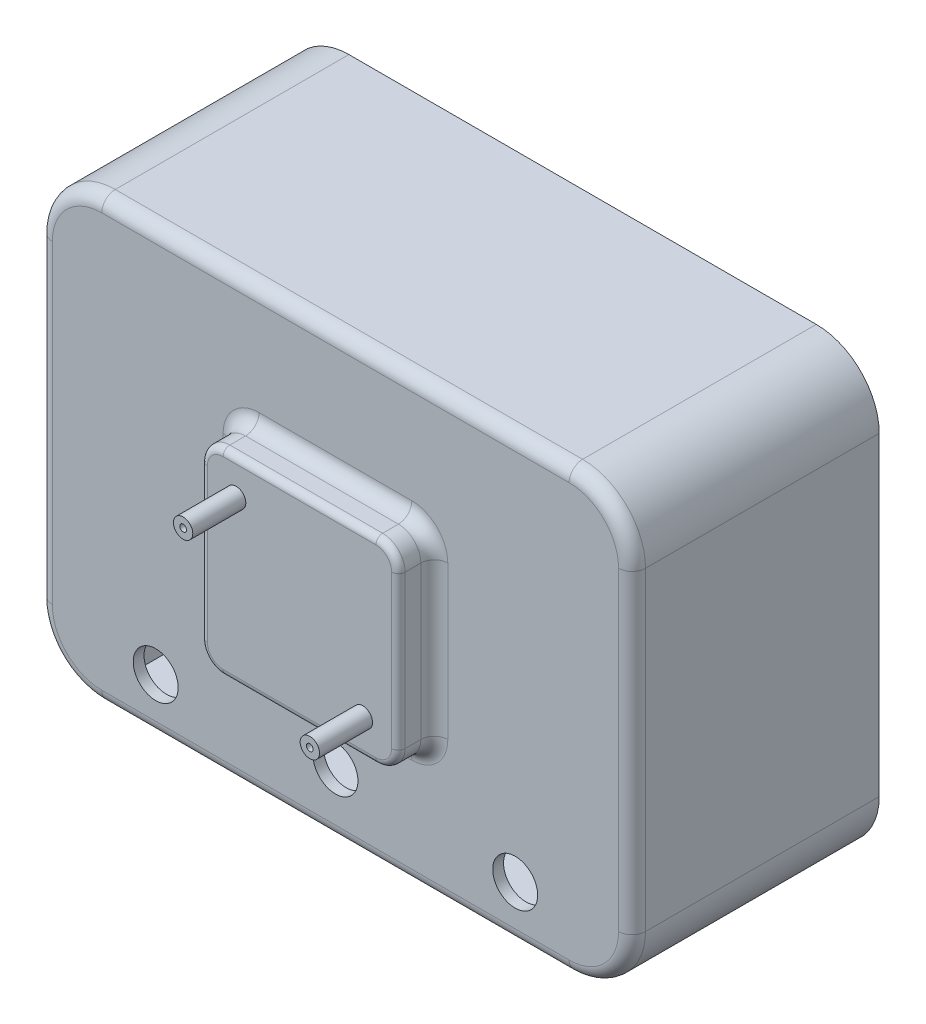
SolidWorks part; units mm, degrees
ref_plane "Front Plane" through (0, 0, 0) normal (0, 0, 1) x (1, 0, 0)
ref_plane "Top Plane" through (0, 0, 0) normal (0, 1, 0) x (1, 0, 0)
ref_plane "Right Plane" through (0, 0, 0) normal (1, 0, 0) x (0, 0, -1)
sketch "Sketch1" plane through (0, 0, 0) normal (0, 0, 1) x (1, 0, 0)
  line L1 (-66, -49) -> (66, -49)
  line L2 (-66, -49) -> (-66, 49)
  line L3 (-66, 49) -> (66, 49)
  line L4 (66, -49) -> (66, 49)
extrude "Boss-Extrude1" add sketch "Sketch1" along normal blind 55
fillet "Fillet1" radius 14 4 edges at (-66, 49, 27.5) (66, 49, 27.5) (66, -49, 27.5) (-66, -49, 27.5)
sketch "Sketch7" plane through (0, 0, 0) normal (0, 0, 1) x (1, 0, 0)
  circle A0 centre (-27.75, -42.789) radius 6
  circle A1 centre (27.75, -42.789) radius 6
  circle A2 centre (-27.75, 42.789) radius 6
  circle A3 centre (27.75, 42.789) radius 6
extrude "Boss-Extrude2" add sketch "Sketch7" along normal blind 6
sketch "Sketch8" plane through (0, 0, 6) normal (0, 0, 1) x (1, 0, 0)
  circle A0 centre (-27.75, -42.789) radius 2.25
  circle A1 centre (27.75, -42.789) radius 2.25
  circle A2 centre (-27.75, 42.789) radius 2.25
  circle A3 centre (27.75, 42.789) radius 2.25
extrude "Cut-Extrude10" cut sketch "Sketch8" against normal blind 6.2
sketch "Sketch9" plane through (0, 0, 6) normal (0, 0, 1) x (1, 0, 0)
  circle A0 centre (-27.75, -42.789) radius 4
  circle A1 centre (27.75, -42.789) radius 4
  circle A2 centre (-27.75, 42.789) radius 4
  circle A3 centre (27.75, 42.789) radius 4
extrude "Cut-Extrude11" cut sketch "Sketch9" against normal blind 3
fillet "Fillet2" radius 3 8 edges at (-66, 0, 55) (0, -49, 55) (66, 0, 55) (0, 49, 55) (-61.8995, -44.8995, 55) (61.8995, -44.8995, 55) (61.8995, 44.8995, 55) (-61.8995, 44.8995, 55)
sketch "Sketch10" plane through (0, 0, 55) normal (0, 0, 1) x (1, 0, 0)
  line L1 (-22, -22) -> (22, -22)
  line L2 (-22, -22) -> (-22, 22)
  line L3 (-22, 22) -> (22, 22)
  line L4 (22, -22) -> (22, 22)
extrude "Boss-Extrude3" add sketch "Sketch10" along normal blind 8
fillet "Fillet3" radius 5 4 edges at (-22, 22, 59) (22, 22, 59) (22, -22, 59) (-22, -22, 59)
fillet "Fillet4" radius 1.5 8 edges at (-22, 0, 63) (0, -22, 63) (22, 0, 63) (0, 22, 63) (-20.5355, -20.5355, 63) (20.5355, -20.5355, 63) (20.5355, 20.5355, 63) (-20.5355, 20.5355, 63)
sketch "Sketch11" plane through (0, 0, 63) normal (0, 0, 1) x (1, 0, 0)
  circle A0 centre (-14.1, 14.1) radius 2.15
  circle A1 centre (14.1, -14.1) radius 2.15
extrude "Boss-Extrude4" add sketch "Sketch11" along normal blind 11.8
sketch "Sketch12" plane through (0, 0, 74.8) normal (0, 0, 1) x (1, 0, 0)
  circle A0 centre (-14.1, 14.1) radius 0.75
  circle A1 centre (14.1, -14.1) radius 0.75
extrude "Cut-Extrude12" cut sketch "Sketch12" against normal blind 11.3
sketch "Sketch13" plane through (0, 0, 55) normal (0, 0, 1) x (1, 0, 0)
  circle A0 centre (-40, -37) radius 5
  circle A1 centre (40, -37) radius 5
  circle A2 centre (0, -35) radius 5
extrude "Cut-Extrude13" cut sketch "Sketch13" against normal blind 3.2
fillet "Fillet5" radius 3 8 edges at (-22, 0, 55) (0, -22, 55) (22, 0, 55) (0, 22, 55) (-20.5355, 20.5355, 55) (20.5355, 20.5355, 55) (20.5355, -20.5355, 55) (-20.5355, -20.5355, 55)
sketch "Sketch14" plane through (0, 0, 0) normal (0, 0, -1) x (-1, 0, 0)
  line L1 (-52, -46) -> (52, -46)
  line L2 (-52, -46) -> (-52, 46)
  line L3 (-52, 46) -> (52, 46)
  line L4 (52, -46) -> (52, 46)
extrude "Cut-Extrude14" cut sketch "Sketch14" against normal blind 52.6
sketch "Sketch15" plane through (0, 0, 0) normal (0, 0, -1) x (-1, 0, 0)
  line L1 (-63, -35) -> (63, -35)
  line L2 (-63, -35) -> (-63, 35)
  line L3 (-63, 35) -> (63, 35)
  line L4 (63, -35) -> (63, 35)
extrude "Cut-Extrude15" cut sketch "Sketch15" against normal blind 52.6
sketch "Sketch17" plane through (0, 0, 0) normal (0, 0, 1) x (1, 0, 0)
  circle A0 centre (-27.75, -42.789) radius 6.2
  circle A1 centre (27.75, -42.789) radius 6.2
  circle A2 centre (-27.75, 42.789) radius 6.2
  circle A3 centre (27.75, 42.789) radius 6.2
extrude "Boss-Extrude5" add sketch "Sketch17" along normal blind 6
sketch "Sketch18" plane through (0, 0, 6) normal (0, 0, 1) x (1, 0, 0)
  circle A0 centre (-27.75, -42.789) radius 2.25
  circle A1 centre (27.75, -42.789) radius 2.25
  circle A2 centre (-27.75, 42.789) radius 2.25
  circle A3 centre (27.75, 42.789) radius 2.25
extrude "Cut-Extrude17" cut sketch "Sketch18" against normal blind 6.2
sketch "Sketch19" plane through (0, 0, 6) normal (0, 0, 1) x (1, 0, 0)
  circle A0 centre (-27.75, -42.789) radius 4
  circle A1 centre (27.75, -42.789) radius 4
  circle A2 centre (-27.75, 42.789) radius 4
  circle A3 centre (27.75, 42.789) radius 4
extrude "Cut-Extrude18" cut sketch "Sketch19" against normal blind 3
